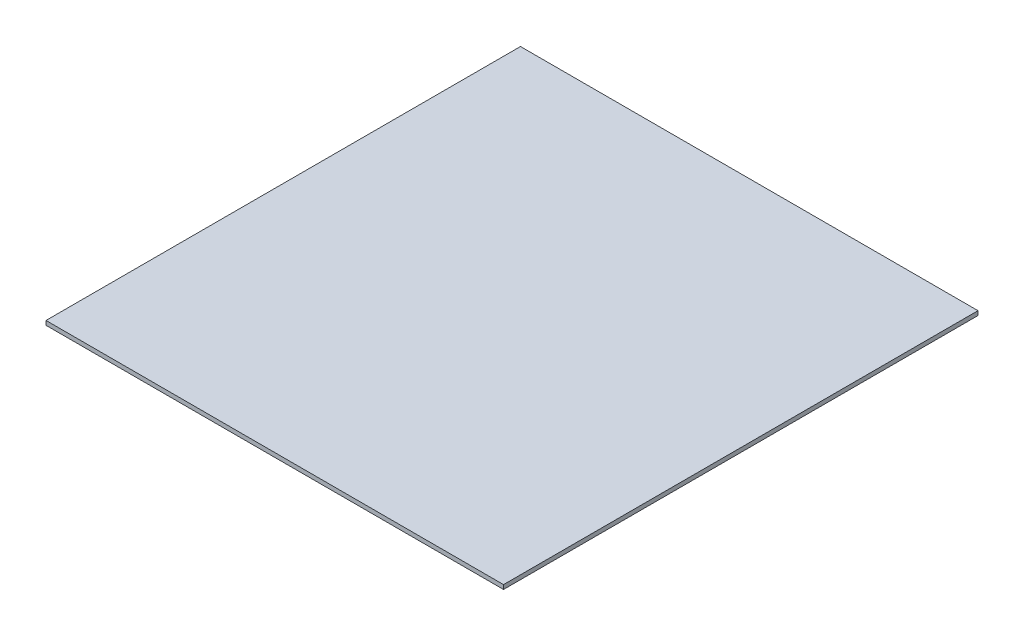
SolidWorks part; units mm, degrees
material "ABS PC"
ref_plane "Front Plane" through (0, 0, 0) normal (0, 0, 1) x (1, 0, 0)
ref_plane "Top Plane" through (0, 0, 0) normal (0, 1, 0) x (1, 0, 0)
ref_plane "Right Plane" through (0, 0, 0) normal (1, 0, 0) x (0, 0, -1)
sketch "Sketch1" plane through (0, 0, 0) normal (0, 1, 0) x (1, 0, 0)
  line L1 (0, 0) -> (342.9, 0)
  line L2 (0, 0) -> (0, 355.6)
  line L3 (0, 355.6) -> (342.9, 355.6)
  line L4 (342.9, 0) -> (342.9, 355.6)
  dimension "D1" = 342.9
  dimension "D2" = 355.6
extrude "Boss-Extrude1" add sketch "Sketch1" along normal blind 3.175
